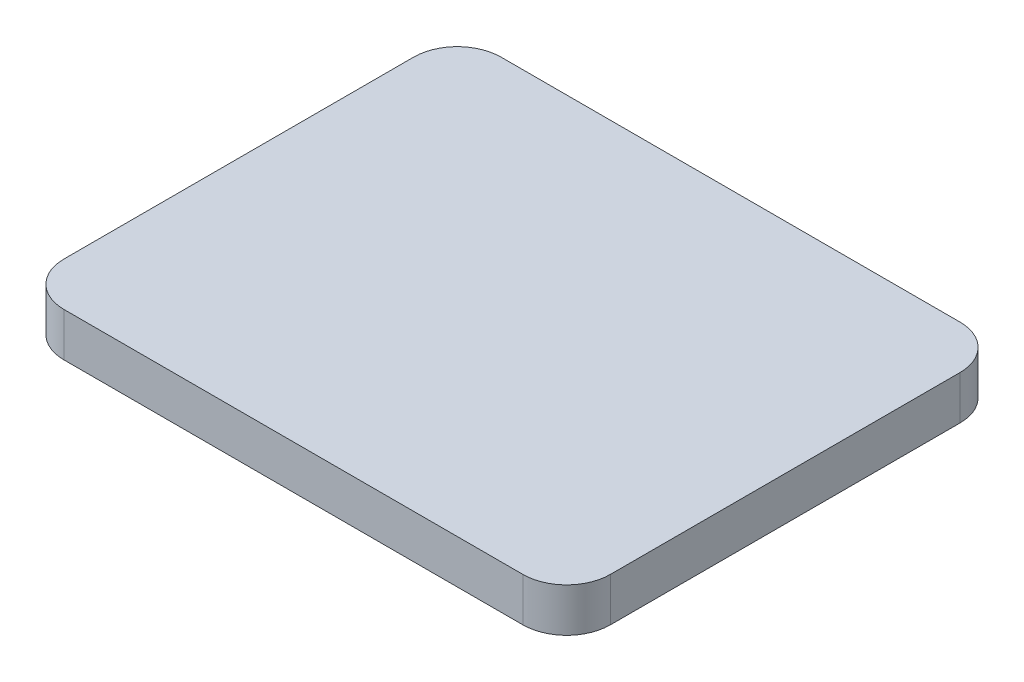
SolidWorks part; units mm, degrees
ref_plane "Front Plane" through (0, 0, 0) normal (0, 0, 1) x (1, 0, 0)
ref_plane "Top Plane" through (0, 0, 0) normal (0, 1, 0) x (1, 0, 0)
ref_plane "Right Plane" through (0, 0, 0) normal (1, 0, 0) x (0, 0, -1)
sketch "Sketch1" plane through (0, 0, 0) normal (0, 1, 0) x (1, 0, 0)
  line L0 (-15.875, 12.7) -> (15.875, -12.7) construction
  line L1 (-15.875, -12.7) -> (15.875, -12.7)
  line L2 (-15.875, -12.7) -> (-15.875, 12.7)
  line L3 (-15.875, 12.7) -> (15.875, 12.7)
  line L4 (15.875, -12.7) -> (15.875, 12.7)
  point P4 (0, 0)
  dimension "D1" = 25.4
  dimension "D2" = 31.75
extrude "Boss-Extrude1" add sketch "Sketch1" along normal blind 2.54
fillet "Fillet1" radius 2.54 4 edges at (15.875, 1.27, -12.7) (15.875, 1.27, 12.7) (-15.875, 1.27, 12.7) (-15.875, 1.27, -12.7)
